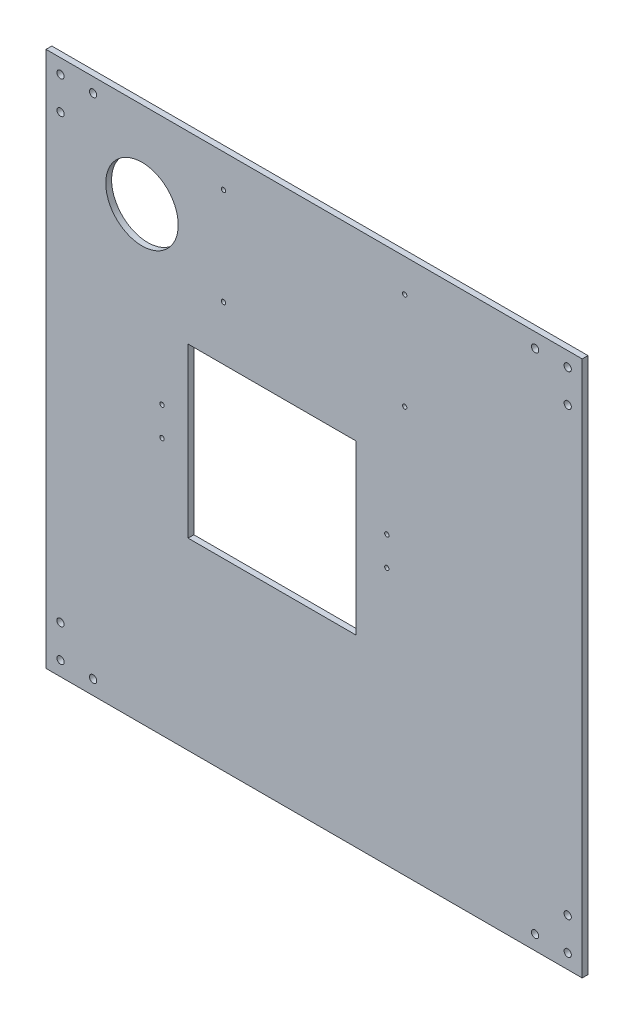
SolidWorks part; units mm, degrees
ref_plane "前视基准面" through (0, 0, 0) normal (0, 0, 1) x (1, 0, 0)
ref_plane "上视基准面" through (0, 0, 0) normal (0, 1, 0) x (1, 0, 0)
ref_plane "右视基准面" through (0, 0, 0) normal (1, 0, 0) x (0, 0, -1)
sketch "草图1" plane through (0, 0, 0) normal (0, 0, 1) x (1, 0, 0)
  line L1 (185, -185) -> (-185, -185)
  line L2 (185, -185) -> (185, 185)
  line L3 (185, 185) -> (-185, 185)
  line L4 (-185, -185) -> (-185, 185)
  line L5 (185, -185) -> (-185, 185) construction
  line L6 (185, 185) -> (-185, -185) construction
  point P0 (0, 0)
  dimension "D1" = 370
  dimension "D2" = 370
extrude "凸台-拉伸1" add sketch "草图1" along normal blind 4
sketch "草图2" plane through (0, 0, 4) normal (0, 0, 1) x (1, 0, 0)
  line L0 (-165, -175) -> (-152.5, -175) construction
  line L1 (-185, -185) -> (-165, -185) construction
  line L2 (-185, -185) -> (-185, -165) construction
  line L3 (-185, -165) -> (-165, -165) construction
  line L4 (-165, -185) -> (-165, -165) construction
  line L5 (-175, -165) -> (-175, -152.5) construction
  circle A0 centre (-175, -175) radius 2.5
  circle A1 centre (-152.5, -175) radius 2.5
  circle A2 centre (-175, -152.5) radius 2.5
  circle A3 centre (-152.5, 175) radius 2.5
  circle A4 centre (-175, 152.5) radius 2.5
  circle A5 centre (-175, 175) radius 2.5
  circle A6 centre (175, 152.5) radius 2.5
  circle A7 centre (152.5, 175) radius 2.5
  circle A8 centre (175, 175) radius 2.5
  circle A9 centre (152.5, -175) radius 2.5
  circle A10 centre (175, -152.5) radius 2.5
  circle A11 centre (175, -175) radius 2.5
  point P34 (0, 0)
  dimension "D3" = 10
  dimension "D4" = 10
  dimension "D5" = 5
  dimension "D6" = 12.5
  dimension "D7" = 5
  dimension "D9" = 5
  dimension "D1" = 20
  dimension "D2" = 20
  dimension "D8" = 12.5
  dimension "D10" = 4
extrude "切除-拉伸1" cut sketch "草图2" against normal through all
sketch "草图4" plane through (0, 0, 0) normal (0, 0, -1) x (-1, 0, 0)
  line L0 (-29.0438, -58.09) -> (86.9562, -58.09)
  line L1 (86.9562, -58.09) -> (86.9562, 57.91)
  line L2 (86.9562, 57.91) -> (-29.0438, 57.91)
  line L3 (-29.0438, 57.91) -> (-29.0438, -58.09)
extrude "切除-拉伸5" cut sketch "草图4" against normal through all
sketch "草图6" plane through (0, 0, 0) normal (0, 0, -1) x (-1, 0, 0)
  line L1 (62.5, 95.2498) -> (-62.5, 95.2498) construction
  line L2 (62.5, 95.2498) -> (62.5, 162.2498) construction
  line L3 (62.5, 162.2498) -> (-62.5, 162.2498) construction
  line L4 (-62.5, 95.2498) -> (-62.5, 162.2498) construction
  line L5 (62.5, 95.2498) -> (-62.5, 162.2498) construction
  line L6 (62.5, 162.2498) -> (-62.5, 95.2498) construction
  circle A0 centre (-62.5, 162.2498) radius 1.5
  circle A1 centre (-62.5, 95.2498) radius 1.5
  circle A2 centre (62.5, 95.2498) radius 1.5
  circle A3 centre (62.5, 162.2498) radius 1.5
  point P0 (0, 128.7498)
  dimension "D3" = 3
  dimension "D4" = 3
  dimension "D5" = 3
  dimension "D6" = 3
  dimension "D1" = 67
  dimension "D2" = 125
extrude "切除-拉伸7" cut sketch "草图6" against normal through all
sketch "草图7" plane through (0, 0, 0) normal (0, 0, -1) x (-1, 0, 0)
  circle A0 centre (118.7699, 125.6318) radius 25
  dimension "D1" = 50
extrude "切除-拉伸8" cut sketch "草图7" against normal through all
sketch "草图8" plane through (0, 0, 0) normal (0, 0, -1) x (-1, 0, 0)
  circle A0 centre (-50.2134, -7.306) radius 1.5
  circle A1 centre (-50.2134, 12.694) radius 1.5
  circle A2 centre (104.9562, -7.3087) radius 1.5
  circle A3 centre (104.9562, 12.6913) radius 1.5
extrude "切除-拉伸9" cut sketch "草图8" against normal blind 10
